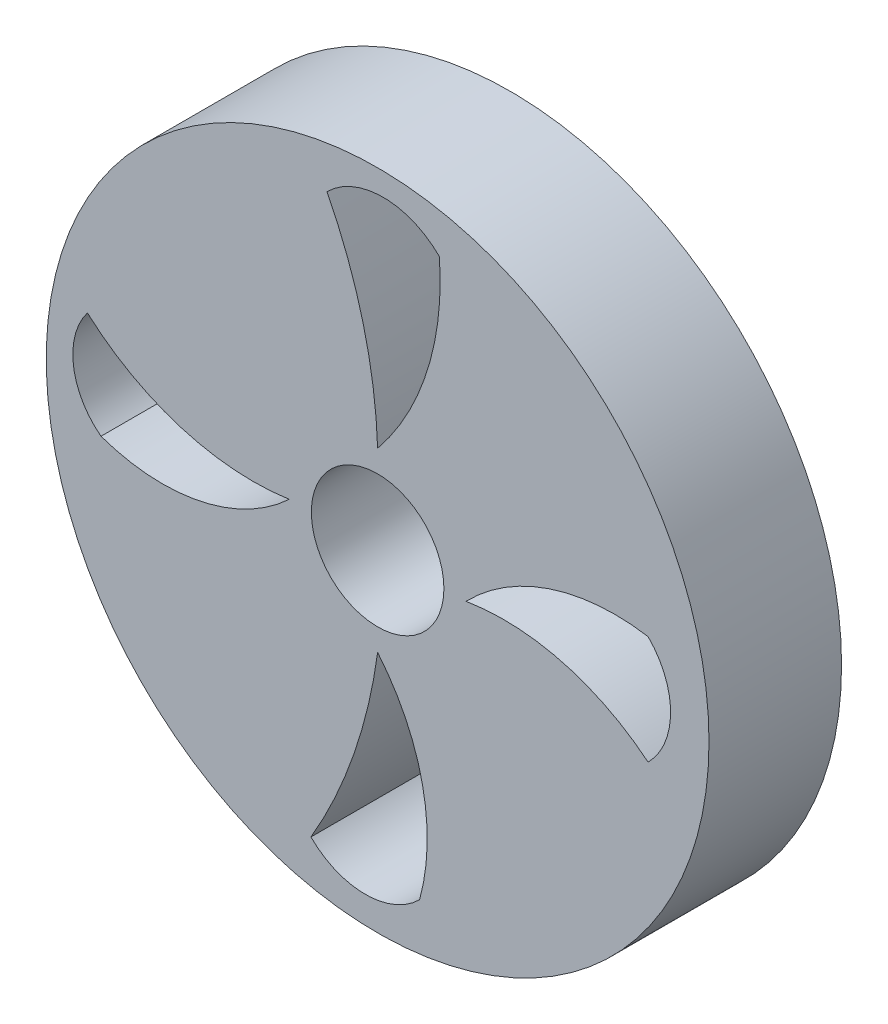
SolidWorks part; units mm, degrees
ref_plane "Front Plane" through (0, 0, 0) normal (0, 0, 1) x (1, 0, 0)
ref_plane "Top Plane" through (0, 0, 0) normal (0, 1, 0) x (1, 0, 0)
ref_plane "Right Plane" through (0, 0, 0) normal (1, 0, 0) x (0, 0, -1)
sketch "Sketch1" plane through (0, 0, 0) normal (0, 0, 1) x (1, 0, 0)
  circle A0 centre (0, 0) radius 75
  circle A1 centre (0, 0) radius 15
  dimension "D1" = 150
extrude "Boss-Extrude1" add sketch "Sketch1" along normal blind 30
sketch "Sketch3" plane through (0, 0, 30) normal (0, 0, 1) x (1, 0, 0)
  arc A8 (20, 0) -> (61.2145, -10.9012) centre (28.5655, -50.9772) cw
  arc A9 (61.2145, 13.6964) -> (61.2145, -10.9012) centre (48.9157, 1.3976) cw
  arc A10 (0, 20) -> (13.9759, 64.5687) centre (-48.9227, 59.8169) ccw
  arc A12 (0, 20) -> (-11.4602, 64.5687) centre (-106.1267, 16.4687) ccw
  arc A13 (-11.4602, 64.5687) -> (13.9759, 64.5687) centre (1.2578, 51.8506) cw
  arc A14 (-20, 0) -> (-62.6121, -8.9446) centre (-48.6879, 30.6952) cw
  arc A15 (-20, 0) -> (-65.6868, 13.6964) centre (-28.1875, 55.7356) cw
  arc A16 (-65.6868, 13.6964) -> (-62.6121, -8.9446) centre (-52.8289, 3.9133) ccw
  arc A17 (20, 0) -> (61.2145, 13.6964) centre (53.707, -32.571) cw
  arc A18 (0, -20) -> (9.5036, -63.7302) centre (-37.0747, -50.955) cw
  arc A19 (0, -20) -> (-15.094, -63.7302) centre (-116.5397, -4.2449) cw
  arc A20 (-15.094, -63.7302) -> (9.5036, -63.7302) centre (-2.7952, -51.4314) ccw
  point P8 (0, 0)
  point P10 (0, 0)
  point P13 (0, 0)
extrude "Cut-Extrude1" cut sketch "Sketch3" against normal blind 30
